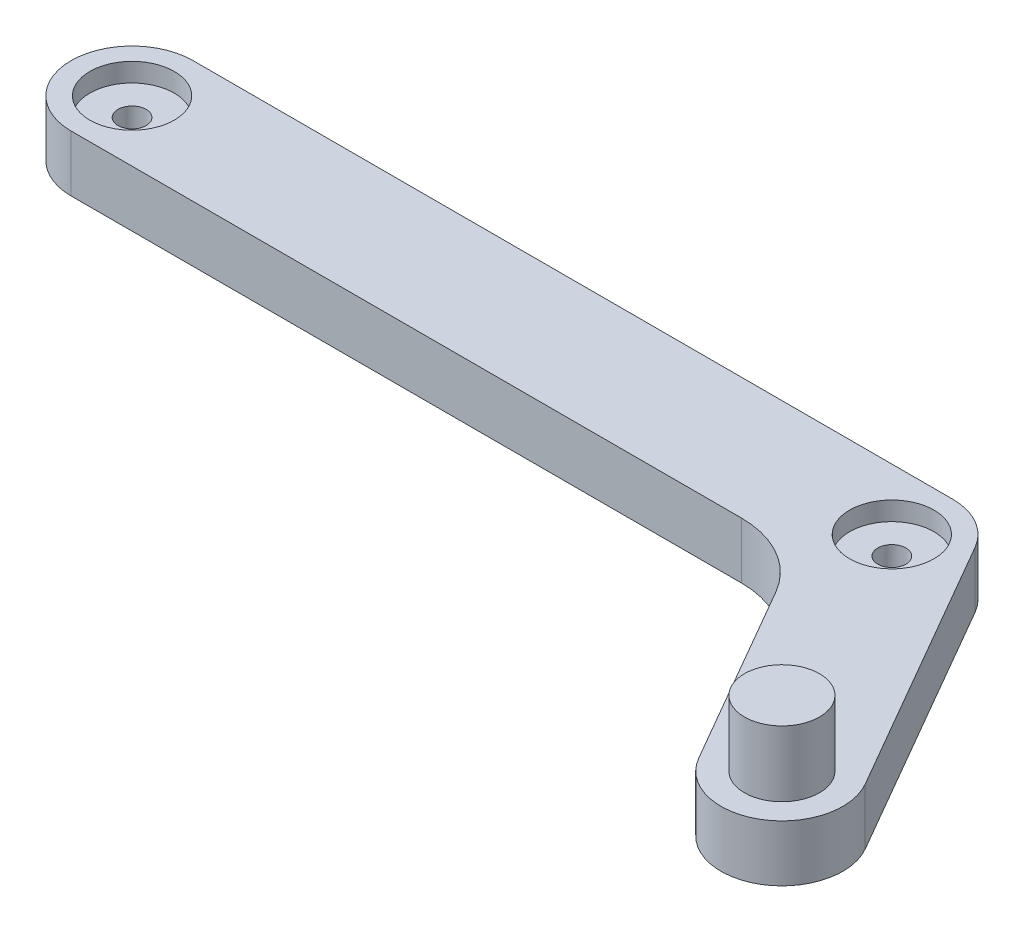
SolidWorks part; units mm, degrees
ref_plane "Front Plane" through (0, 0, 0) normal (0, 0, 1) x (1, 0, 0)
ref_plane "Top Plane" through (0, 0, 0) normal (0, 1, 0) x (1, 0, 0)
ref_plane "Right Plane" through (0, 0, 0) normal (1, 0, 0) x (0, 0, -1)
sketch "Sketch1" plane through (0, 0, 0) normal (0, 1, 0) x (1, 0, 0)
  line L0 (0, 0) -> (81, 0) construction
  line L1 (0, 6.5) -> (81, 6.5)
  line L2 (0, -6.5) -> (71.4737, -6.5)
  line L3 (81, 0) -> (97, -27.7128) construction
  line L4 (80.134, -11.5) -> (91.3708, -30.9628)
  line L5 (86.6292, 3.25) -> (102.6292, -24.4628)
  line L6 (75.3708, -3.25) -> (91.3708, -30.9628) construction
  circle A0 centre (0, 0) radius 1.5
  arc A1 (0, 6.5) -> (0, -6.5) centre (0, 0) ccw
  circle A3 centre (81, 0) radius 1.5
  circle A4 centre (0, 0) radius 6.5 construction
  circle A5 centre (97, -27.7128) radius 1.5 construction
  arc A9 (81.4913, -6.4814) -> (85.8238, -4.3567) centre (81, 0) ccw [skipped]
  arc A10 (81, 6.5) -> (84.25, -5.6292) centre (81, 0) ccw construction
  circle A11 centre (81, 0) radius 6.5 construction
  arc A12 (91.3708, -30.9628) -> (102.6292, -24.4628) centre (97, -27.7128) ccw
  arc A13 (86.6292, 3.25) -> (81, 6.5) centre (81, 0) ccw
  arc A14 (80.134, -11.5) -> (71.4737, -6.5) centre (71.4737, -16.5) ccw
  circle A15 centre (97, -27.7128) radius 6.5 construction
  dimension "D1" = 3
  dimension "D5" = 3
  dimension "D7" = 10
  dimension "D4" = 81
  dimension "D8" = 32
  dimension "D6" = 120
  dimension "D2" = 5
  dimension "D11" = 6.5
  dimension "D3" = 2
extrude "Boss-Extrude1" add sketch "Sketch1" along normal blind 6
sketch "Sketch2" plane through (0, 6, 0) normal (0, 1, 0) x (1, 0, 0)
  circle A5 centre (0, 0) radius 4.5
  circle A6 centre (0, 0) radius 4.5
  circle A8 centre (81, 0) radius 4.5
  circle A9 centre (81, 0) radius 4.5
  dimension "D1" = 3
  dimension "D2" = 3
extrude "Cut-Extrude1" cut sketch "Sketch2" against normal blind 2
sketch "Sketch3" plane through (0, 6, 0) normal (0, 1, 0) x (1, 0, 0)
  circle A0 centre (97, -27.7128) radius 4
  arc A2 (91.3708, -30.9628) -> (102.6292, -24.4628) centre (97, -27.7128) ccw construction
  dimension "D1" = 8
extrude "Boss-Extrude2" add sketch "Sketch3" along normal blind 7
